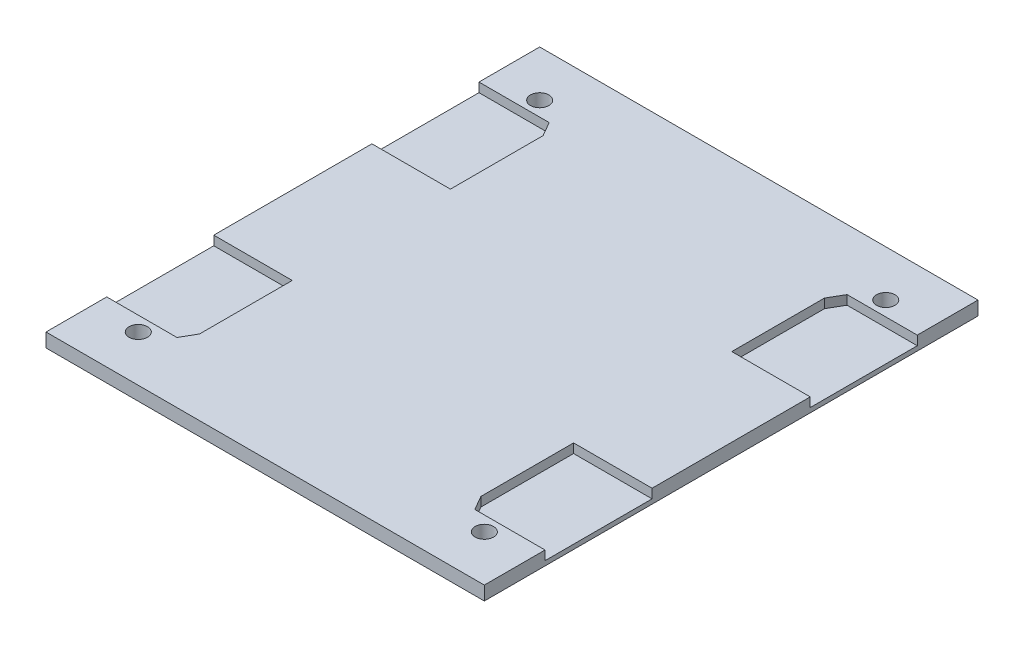
SolidWorks part; units mm, degrees
ref_plane "Front Plane" through (0, 0, 0) normal (0, 0, 1) x (1, 0, 0)
ref_plane "Top Plane" through (0, 0, 0) normal (0, 1, 0) x (1, 0, 0)
ref_plane "Right Plane" through (0, 0, 0) normal (1, 0, 0) x (0, 0, -1)
sketch "Sketch2" plane through (0, 0, 0) normal (0, 1, 0) x (1, 0, 0)
  line L0 (37.5, -43.5) -> (47.5, -43.5)
  line L1 (-47.5, -53.5) -> (47.5, -53.5)
  line L2 (-47.5, -53.5) -> (-47.5, 53.5)
  line L3 (-47.5, 53.5) -> (47.5, 53.5)
  line L4 (47.5, -53.5) -> (47.5, 53.5)
  line L5 (-47.5, -53.5) -> (47.5, 53.5) construction
  line L6 (-47.5, 53.5) -> (47.5, -53.5) construction
  line L7 (37.5, -43.5) -> (37.5, -53.5)
  line L8 (-55, 0) -> (55, 0) construction
  line L9 (0, -55) -> (0, 55) construction
  line L15 (-60, 66) -> (60, 66)
  line L16 (-60, 66) -> (-60, -66)
  line L17 (-60, -66) -> (60, -66)
  line L18 (60, 66) -> (60, -66)
  line L19 (-60, 66) -> (60, -66) construction
  line L20 (-60, -66) -> (60, 66) construction
  circle A1 centre (37.5, -43.5) radius 2
  circle A2 centre (37.5, 43.5) radius 2
  circle A3 centre (-37.5, -43.5) radius 2
  circle A4 centre (-37.5, 43.5) radius 2
  point P0 (0, 0)
  point P20 (0, 0)
  point P21 (0, 0)
  dimension "D3" = 10
  dimension "D5" = 4
  dimension "D1" = 95
  dimension "D2" = 107
  dimension "D4" = 10
  dimension "D6" = 120
  dimension "D7" = 132
extrude "Boss-Extrude1" add sketch "Sketch2" along normal blind 3 contours A1 L0 L4 L3 L2 L1 L7 A4 A2 A3 | A1 L7 L1 L4 L0
sketch "Sketch3" plane through (0, 3, 0) normal (0, 1, 0) x (1, 0, 0)
  line L5 (-47.515, 40.2371) -> (-32.4121, 40.2371) construction
  line L6 (-47.5, -53.5) -> (-47.5, 53.5) construction
  line L10 (-47.5, 17.2402) -> (-47.5, 40.2371)
  line L11 (-47.6, 40.3371) -> (-32.2822, 40.3371)
  line L12 (-32.2822, 40.3371) -> (-30.49, 37.2328)
  line L13 (-30.49, 17.1402) -> (-30.49, 37.2328)
  line L14 (-47.6, 17.1402) -> (-30.49, 17.1402)
  line L15 (-47.6, 17.1402) -> (-47.6, 40.3371)
  line L16 (-47.5, 40.2371) -> (-32.34, 40.2371) construction
  line L17 (-47.5, 17.2402) -> (-30.59, 17.2402) construction
  line L18 (-30.59, 17.2402) -> (-30.59, 37.206) construction
  line L19 (-32.34, 40.2371) -> (-30.59, 37.206) construction
  line L20 (0, 62.7045) -> (0, 59.4045) construction
  line L21 (32.2822, 40.3371) -> (30.49, 37.2328)
  line L22 (30.49, 17.1402) -> (30.49, 37.2328)
  line L23 (47.6, 17.1402) -> (30.49, 17.1402)
  line L24 (47.5, 17.2402) -> (47.5, 40.2371)
  line L25 (47.6, 40.3371) -> (32.2822, 40.3371)
  line L26 (-130.0965, 0) -> (-126.7965, 0) construction
  line L27 (47.5, -17.2402) -> (47.5, -40.2371)
  line L28 (47.6, -17.1402) -> (30.49, -17.1402)
  line L29 (30.49, -17.1402) -> (30.49, -37.2328)
  line L30 (32.2822, -40.3371) -> (30.49, -37.2328)
  line L31 (47.6, -40.3371) -> (32.2822, -40.3371)
  line L32 (-30.49, -17.1402) -> (-30.49, -37.2328)
  line L33 (-32.2822, -40.3371) -> (-30.49, -37.2328)
  line L34 (-47.6, -40.3371) -> (-32.2822, -40.3371)
  line L35 (-47.5, -17.2402) -> (-47.5, -40.2371)
  line L36 (-47.6, -17.1402) -> (-30.49, -17.1402)
  line M16 (47.5, -53.5) -> (47.5, 53.5)
  line M18 (-47.5, 53.5) -> (-47.5, -53.5)
  dimension "D1" = 0.1
extrude "Cut-Extrude1" cut sketch "Sketch3" against normal blind 2 contours L14 L13 L12 L11 M18 | L25 L21 L22 L23 M16 | L31 L28 L29 L30 M16 | L36 L34 L33 L32 M18
